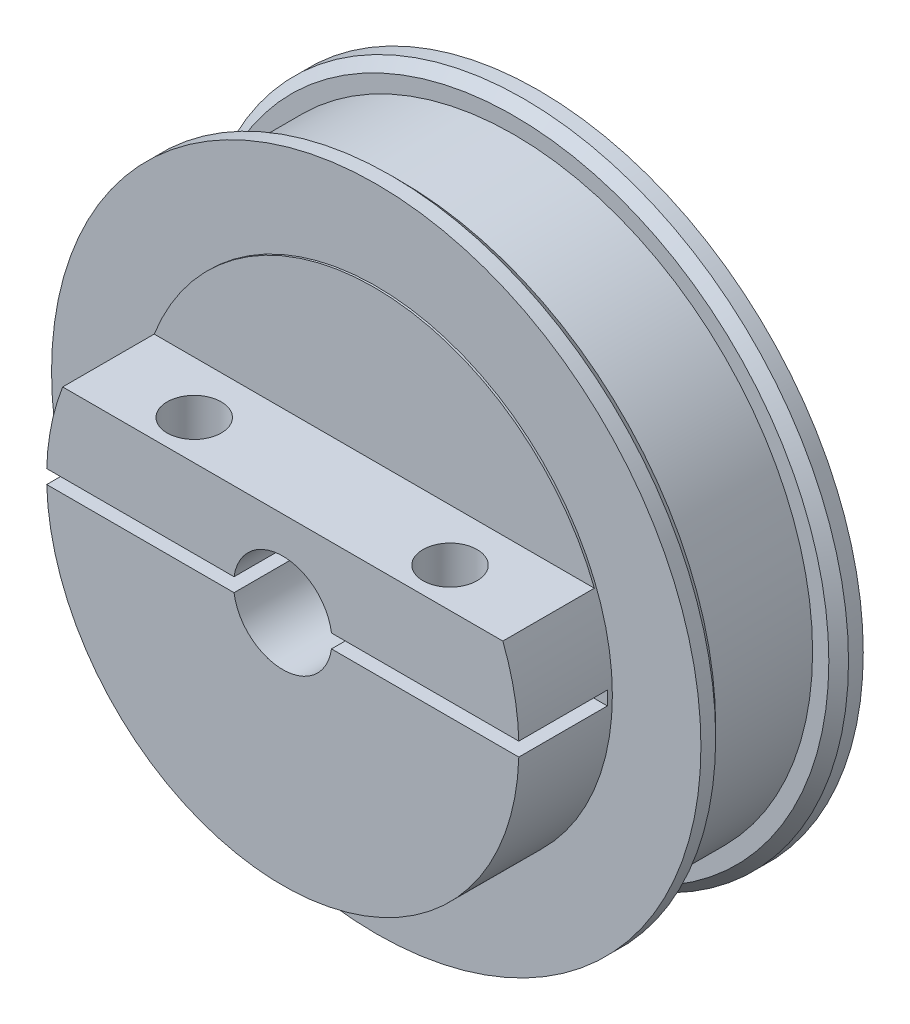
SolidWorks part; units mm, degrees
material "SKD11淬火HRC56-60"
ref_plane "前基準面" through (0, 0, 0) normal (0, 0, 1) x (1, 0, 0)
ref_plane "上基準面" through (0, 0, 0) normal (0, 1, 0) x (1, 0, 0)
ref_plane "右基準面" through (0, 0, 0) normal (1, 0, 0) x (0, 0, -1)
sketch "草图1" plane through (0, 0, 0) normal (0, 0, 1) x (1, 0, 0)
  circle A0 centre (0, 0) radius 33
  dimension "D1" = 66
extrude "凸台-拉伸1" add sketch "草图1" along normal blind 2.5
sketch "草图2" plane through (0, 0, 2.5) normal (0, 0, 1) x (1, 0, 0)
  circle A0 centre (0, 0) radius 30.35
  dimension "D1" = 60.7
extrude "凸台-拉伸2" add sketch "草图2" along normal blind 11.5
sketch "草图3" plane through (0, 0, 14) normal (0, 0, 1) x (1, 0, 0)
  circle A1 centre (0, 0) radius 33
  circle A2 centre (0, 0) radius 33
  dimension "D1" = 0
extrude "凸台-拉伸3" add sketch "草图3" along normal blind 2.5
sketch "草图4" plane through (0, 0, 16.5) normal (0, 0, 1) x (1, 0, 0)
  circle A0 centre (0, 0) radius 24
  dimension "D1" = 48
extrude "凸台-拉伸4" add sketch "草图4" along normal blind 9.5
chamfer "倒角1" distance 1 angle 45 2 edges at (33, 0, 2.5) (33, 0, 14)
sketch "草图5" plane through (0, 0, 26) normal (0, 0, 1) x (1, 0, 0)
  circle A0 centre (0, 0) radius 5
  dimension "D1" = 10
extrude "切除-拉伸1" cut sketch "草图5" against normal through all
sketch "草图6" plane through (0, 0, 26) normal (0, 0, 1) x (1, 0, 0)
  line L0 (0, 0) -> (45.5864, 0) construction
  line L1 (-25, 0.7) -> (25, 0.7)
  line L2 (-25, 0.7) -> (-25, -0.7)
  line L3 (-25, -0.7) -> (25, -0.7)
  line L4 (25, 0.7) -> (25, -0.7)
  line L5 (0, 0) -> (0, -18.6563) construction
  dimension "D1" = 1.4
  dimension "D2" = 50
extrude "切除-拉伸2" cut sketch "草图6" against normal blind 9
sketch "草图7" plane through (0, 0.7, 0) normal (0, -1, 0) x (1, 0, 0)
  line L0 (0, 0) -> (0, 31.9292) construction
  line L1 (-33, 0) -> (33, 0) construction
  line L2 (23.9898, 26) -> (-23.9898, 26) construction
  circle A0 centre (-13, 22) radius 2.75
  circle A1 centre (13, 22) radius 2.75
  dimension "D1" = 4
  dimension "D2" = 5.5
  dimension "D3" = 26
extrude "切除-拉伸3" cut sketch "草图7" against normal blind 8
sketch "草图8" plane through (0, 8.7, 0) normal (0, -1, 0) x (1, 0, 0)
  circle A0 centre (-13, 22) radius 5
  circle A1 centre (13, 22) radius 5
  dimension "D1" = 10
extrude "切除-拉伸4" cut sketch "草图8" against normal through all
hole_wizard "M5 螺纹孔1" positions "草图10" profile "草图11" tap size "M5" standard "ISO" end condition through all
sketch "草图10" plane through (0, -0.7, 0) normal (0, 1, 0) x (-1, 0, 0)
  point P0 (13, 22)
  point P5 (-13, 22)
sketch "草图11" plane through (-13, -0.7, 22) normal (1, 0, 0) x (0, 0, 1)
  line L0 (0, 0) -> (0, 32.3)
  line L1 (0, 32.3) -> (2.1, 32.3)
  line L2 (2.1, 32.3) -> (2.1, 0)
  line L5 (2.1, 0) -> (0, 0)
  line L11 (0, -6.35) -> (0, 107.95) construction
  dimension "通孔螺纹孔钻头直径" = 4.2
  dimension "通孔螺纹孔钻头深度" = 32.3
cosmetic thread "孔螺蚊线1" parameters "D2"=5
cosmetic thread "孔螺蚊线2" parameters "D2"=5
sketch "草图12" plane through (0, 0, 26) normal (0, 0, 1) x (1, 0, 0)
  line L0 (0, 0) -> (0, 19.0076) construction
  line L1 (-18, 8.7) -> (-8, 8.7)
  line L2 (-18, 8.7) -> (-18, 22.7)
  line L3 (-18, 22.7) -> (-8, 22.7)
  line L4 (-8, 8.7) -> (-8, 22.7)
  line L5 (-13, 8.7) -> (-13, 6.141) construction
  line L6 (-16, 8.7) -> (-10, 8.7) construction
  line L7 (8, 8.7) -> (8, 22.7)
  line L8 (18, 22.7) -> (8, 22.7)
  line L9 (18, 8.7) -> (18, 22.7)
  line L10 (18, 8.7) -> (8, 8.7)
  dimension "D1" = 10
  dimension "D2" = 14
extrude "切除-拉伸5" cut sketch "草图12" against normal blind 4
sketch "草图13" plane through (0, 0, 26) normal (0, 0, 1) x (1, 0, 0)
  line L0 (8, 8.7) -> (18, 8.7) construction
  line L1 (-38.9537, 25.2764) -> (33.5342, 25.2764)
  line L2 (-38.9537, 25.2764) -> (-38.9537, 8.7)
  line L3 (-38.9537, 8.7) -> (33.5342, 8.7)
  line L4 (33.5342, 25.2764) -> (33.5342, 8.7)
extrude "切除-拉伸6" cut sketch "草图13" against normal blind 9.3
